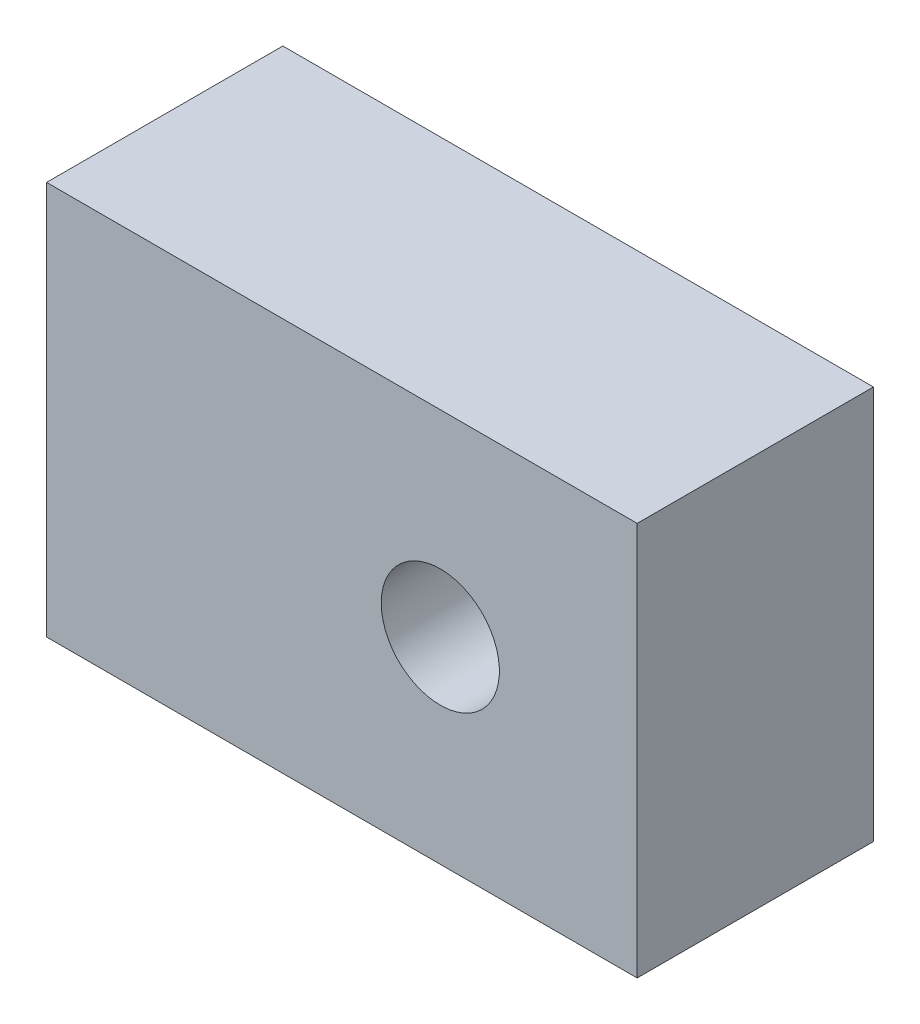
SolidWorks part; units mm, degrees
ref_plane "Front Plane" through (0, 0, 0) normal (0, 0, 1) x (1, 0, 0)
ref_plane "Top Plane" through (0, 0, 0) normal (0, 1, 0) x (1, 0, 0)
ref_plane "Right Plane" through (0, 0, 0) normal (1, 0, 0) x (0, 0, -1)
sketch "Sketch1" plane through (0, 0, 0) normal (0, 0, 1) x (1, 0, 0)
  line L1 (0, 0) -> (15, 0)
  line L2 (0, 0) -> (0, 10)
  line L3 (0, 10) -> (15, 10)
  line L4 (15, 0) -> (15, 10)
  dimension "D1" = 10
  dimension "D2" = 15
extrude "Boss-Extrude1" add sketch "Sketch1" along normal blind 6
sketch "Sketch2" plane through (0, 0, 0) normal (0, 0, -1) x (-1, 0, 0)
  line L0 (-15, 10) -> (0, 10) construction
  line L2 (-15, 0) -> (-15, 10) construction
  circle A0 centre (-10, 5) radius 1.5
  dimension "D1" = 3
  dimension "D2" = 5
  dimension "D3" = 5
extrude "Cut-Extrude1" cut sketch "Sketch2" against normal blind 6
